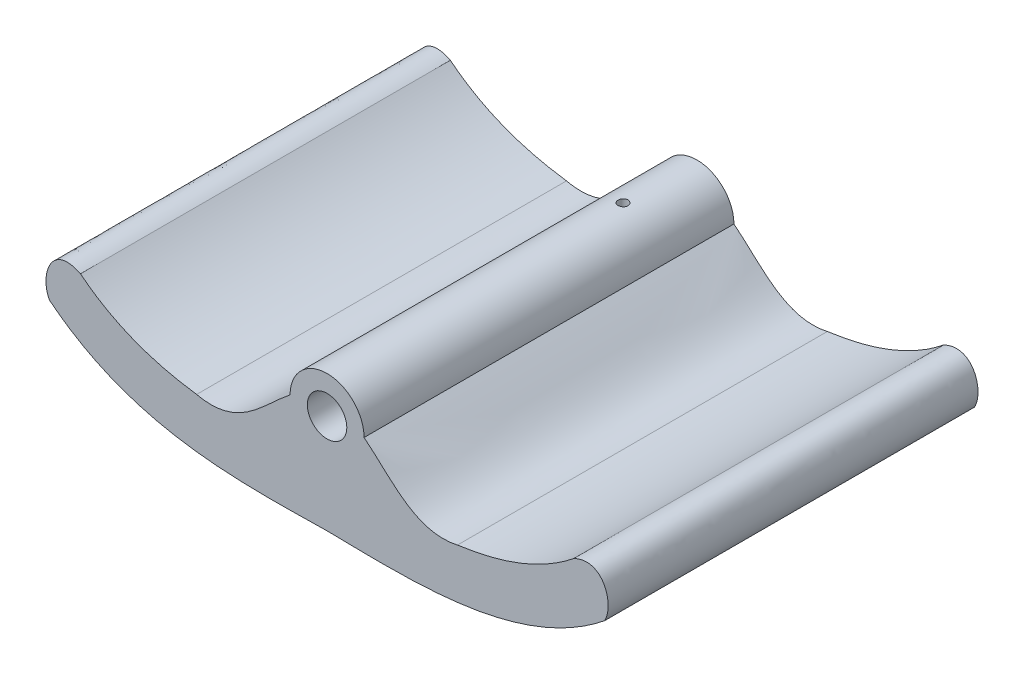
SolidWorks part; units mm, degrees
ref_plane "Front Plane" through (0, 0, 0) normal (0, 0, 1) x (1, 0, 0)
ref_plane "Top Plane" through (0, 0, 0) normal (0, 1, 0) x (1, 0, 0)
ref_plane "Right Plane" through (0, 0, 0) normal (1, 0, 0) x (0, 0, -1)
sketch "Sketch1" plane through (0, 0, 0) normal (0, 0, 1) x (1, 0, 0)
  line L0 (0, 0) -> (0, -10.1391) construction
  line L1 (0, 0) -> (-50, 0) construction
  circle A0 centre (0, 0) radius 4
  circle A1 centre (0, 0) radius 7.5
  spline S0 degree 3 poles (0, -10.1391) (-16.9347, -10.3875) (-35.7541, -11.4685) (-50, 0) knots 0 0 0 0 1 1 1 1
  spline S1 degree 1 poles (0.1467, -20.1381) (-56.2709, -7.7895) knots 0 0 1 1 construction
  spline S2 degree 3 poles (0.1467, -20.1381) (-0.9092, -20.1535) (-2.9971, -20.1904) (-7.3619, -20.2663) (-13.0066, -20.3135) (-20.0511, -20.121) (-27.291, -19.4873) (-34.6644, -18.1972) (-42.0772, -16.015) (-48.173, -13.2424) (-52.8716, -10.367) (-55.1704, -8.6754) (-56.2709, -7.7895) knots 0 0 0 0 0.0625 0.125 0.25 0.375 0.5 0.625 0.75 0.875 0.9375 1 1 1 1
  spline S3 degree 3 poles (-56.2709, -7.7895) (-58.317, -4.1207) (-55.9635, 2.9566) (-50, 0) knots 0 0 0 0 1 1 1 1
  spline S4 degree 3 poles (-0.1467, -20.1381) (0.9092, -20.1535) (2.9971, -20.1904) (7.3619, -20.2663) (13.0066, -20.3135) (20.0511, -20.121) (27.291, -19.4873) (34.6644, -18.1972) (42.0772, -16.015) (48.173, -13.2424) (52.8716, -10.367) (55.1704, -8.6754) (56.2709, -7.7895) knots 0 0 0 0 0.0625 0.125 0.25 0.375 0.5 0.625 0.75 0.875 0.9375 1 1 1 1
  spline S5 degree 3 poles (56.2709, -7.7895) (58.317, -4.1207) (55.9635, 2.9566) (50, 0) knots 0 0 0 0 1 1 1 1
  spline S6 degree 3 poles (0, -10.1391) (16.9347, -10.3875) (35.7541, -11.4685) (50, 0) knots 0 0 0 0 1 1 1 1
  spline S7 degree 3 poles (-7.5, 0) (-13.1334, -4.4619) (-17.7674, -11.3459) (-26.4484, -9.4042) knots 0 0 0 0 1 1 1 1
  spline S8 degree 3 poles (7.5, 0) (13.1334, -4.4619) (17.7674, -11.3459) (26.4484, -9.4042) knots 0 0 0 0 1 1 1 1
  dimension "D1" = 8
  dimension "D2" = 15
  dimension "D4" = 10
  dimension "D3" = 50
extrude "Boss-Extrude1" add sketch "Sketch1" along normal blind 75
sketch "Sketch2" plane through (0, 0, 0) normal (0, 1, 0) x (1, 0, 0)
  line L0 (0, 0) -> (0, -15) construction
  circle A0 centre (0, -15) radius 1
  dimension "D2" = 2
  dimension "D1" = 15
extrude "Cut-Extrude1" cut sketch "Sketch2" along normal blind 75
